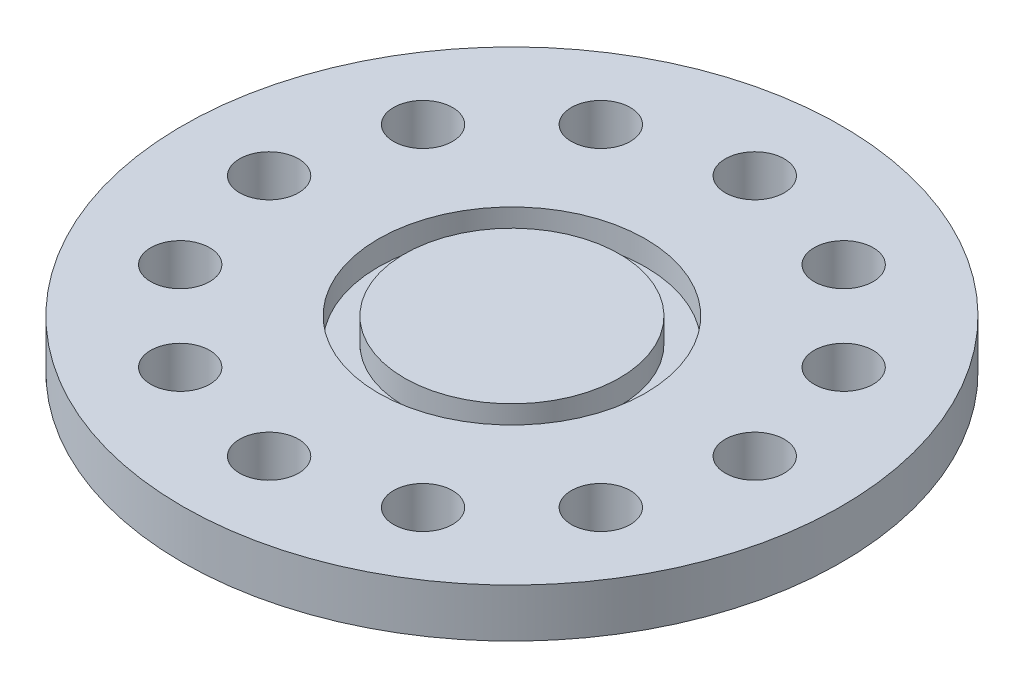
SolidWorks part; units mm, degrees
ref_plane "정면" through (0, 0, 0) normal (0, 0, 1) x (1, 0, 0)
ref_plane "윗면" through (0, 0, 0) normal (0, 1, 0) x (1, 0, 0)
ref_plane "우측면" through (0, 0, 0) normal (1, 0, 0) x (0, 0, -1)
sketch "스케치1" plane through (0, 0, 0) normal (0, 1, 0) x (1, 0, 0)
  circle A0 centre (0, 0) radius 9.5
  circle A1 centre (0, 7) radius 0.85
  circle A2 centre (3.5, 6.0622) radius 0.85
  circle A3 centre (6.0622, 3.5) radius 0.85
  circle A4 centre (7, 0) radius 0.85
  circle A5 centre (6.0622, -3.5) radius 0.85
  circle A6 centre (3.5, -6.0622) radius 0.85
  circle A7 centre (0, -7) radius 0.85
  circle A8 centre (-3.5, -6.0622) radius 0.85
  circle A9 centre (-6.0622, -3.5) radius 0.85
  circle A10 centre (-7, 0) radius 0.85
  circle A11 centre (-6.0622, 3.5) radius 0.85
  circle A12 centre (-3.5, 6.0622) radius 0.85
  point P30 (0, 0)
  dimension "D1" = 19
  dimension "D2" = 1.7
  dimension "D3" = 7
  dimension "D5" = 7
  dimension "D6" = 7
  dimension "D4" = 12
extrude "보스-돌출1" add sketch "스케치1" along normal blind 1.4
sketch "스케치2" plane through (0, 1.4, 0) normal (0, 1, 0) x (1, 0, 0)
  circle A0 centre (0, 0) radius 3.85
  circle A1 centre (0, 0) radius 3.1
  dimension "D1" = 7.7
  dimension "D2" = 6.2
extrude "컷-돌출1" cut sketch "스케치2" against normal blind 0.7
sketch "스케치3" plane through (0, 0, 0) normal (0, -1, 0) x (1, 0, 0)
  line L0 (-0.8, 2.8914) -> (-0.8, 3.8)
  line L1 (-0.8, 3.8) -> (0.8, 3.8)
  line L2 (0.8, 3.8) -> (0.8, 2.8914)
  arc A0 (-0.8, 2.8914) -> (0.8, 2.8914) centre (0, 0) ccw
  point P9 (1.705, 3.1909)
  dimension "D1" = 6
  dimension "D2" = 3.8
  dimension "D3" = 0.8
  dimension "D4" = 1.6
extrude "보스-돌출2" add sketch "스케치3" along normal blind 3
